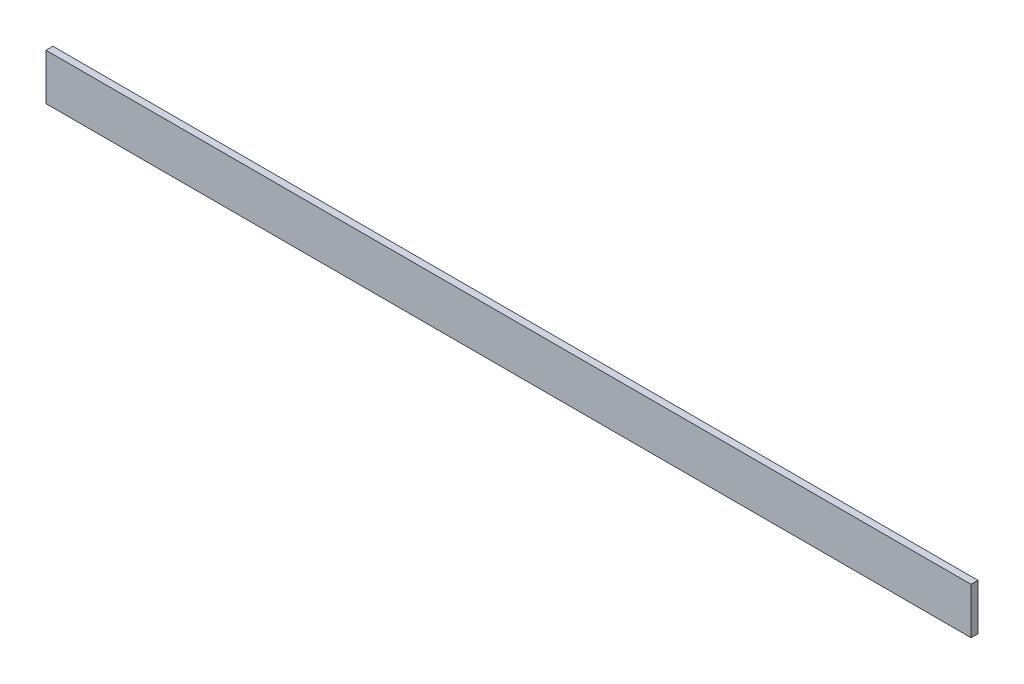
SolidWorks part; units mm, degrees
ref_plane "Ön Düzlem" through (0, 0, 0) normal (0, 0, 1) x (1, 0, 0)
ref_plane "Üst Düzlem" through (0, 0, 0) normal (0, 1, 0) x (1, 0, 0)
ref_plane "Sağ Düzlem" through (0, 0, 0) normal (1, 0, 0) x (0, 0, -1)
sketch "Sketch1" plane through (0, 0, 0) normal (0, 0, 1) x (1, 0, 0)
  line L1 (0, 0) -> (400, 0)
  line L2 (0, 0) -> (0, 20)
  line L3 (0, 20) -> (400, 20)
  line L4 (400, 0) -> (400, 20)
  dimension "D1" = 400
  dimension "D2" = 20
extrude "Boss-Extrude1" add sketch "Sketch1" along normal blind 3
